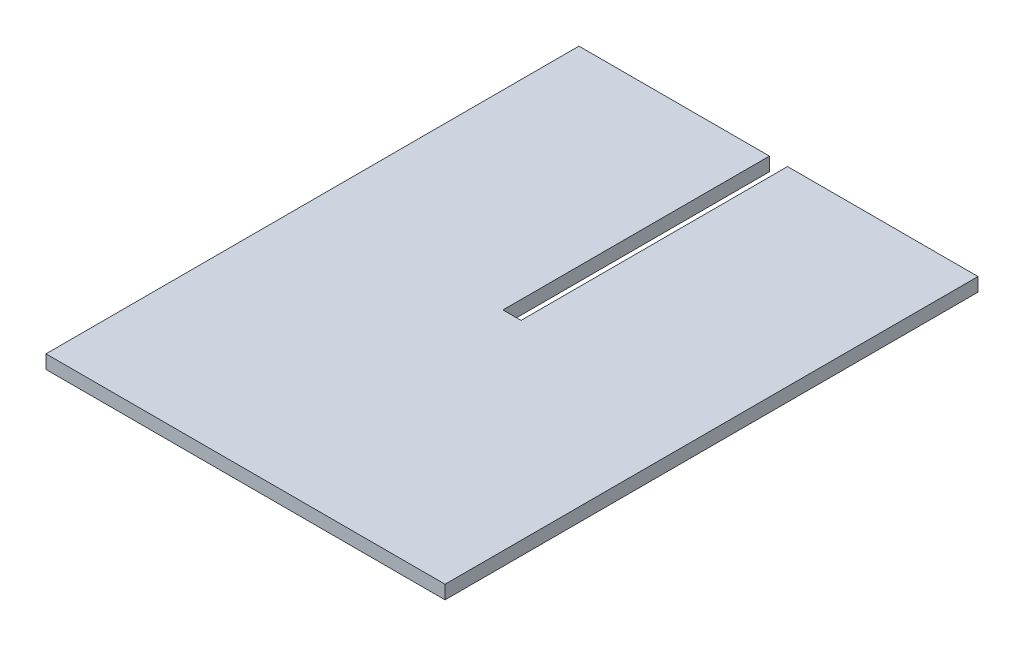
SolidWorks part; units mm, degrees
material "Melamine resin"
ref_plane "Front Plane" through (0, 0, 0) normal (0, 0, 1) x (1, 0, 0)
ref_plane "Top Plane" through (0, 0, 0) normal (0, 1, 0) x (1, 0, 0)
ref_plane "Right Plane" through (0, 0, 0) normal (1, 0, 0) x (0, 0, -1)
sketch "Sketch1" plane through (0, 0, 0) normal (0, 1, 0) x (1, 0, 0)
  line L1 (-22.05, 29.45) -> (22.05, 29.45)
  line L2 (-22.05, 29.45) -> (-22.05, -29.45)
  line L3 (-22.05, -29.45) -> (22.05, -29.45)
  line L4 (22.05, 29.45) -> (22.05, -29.45)
  point P4 (-22.05, 0)
  point P6 (0, 29.45)
  dimension "D1" = 44.1
  dimension "D2" = 58.9
extrude "Boss-Extrude1" add sketch "Sketch1" along normal blind 1.5
sketch "Sketch2" plane through (0, 1.5, 0) normal (0, 1, 0) x (1, 0, 0)
  line L0 (22.05, 29.45) -> (-22.05, 29.45) construction
  line L1 (-1, 29.45) -> (1, 29.45)
  line L2 (-1, 29.45) -> (-1, 0)
  line L3 (-1, 0) -> (1, 0)
  line L4 (1, 29.45) -> (1, 0)
  point P6 (0, 0)
  dimension "D1" = 2
extrude "Cut-Extrude1" cut sketch "Sketch2" against normal up to next
